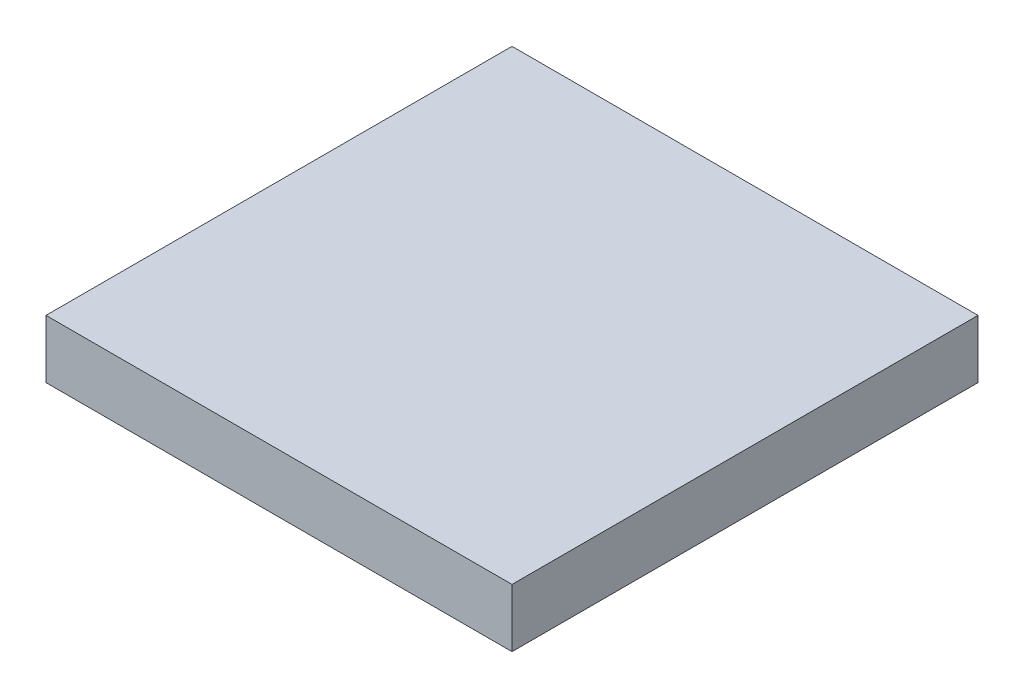
SolidWorks part; units mm, degrees
ref_plane "Front Plane" through (0, 0, 0) normal (0, 0, 1) x (1, 0, 0)
ref_plane "Top Plane" through (0, 0, 0) normal (0, 1, 0) x (1, 0, 0)
ref_plane "Right Plane" through (0, 0, 0) normal (1, 0, 0) x (0, 0, -1)
sketch "Sketch1" plane through (0, 0, 0) normal (0, 1, 0) x (1, 0, 0)
  line L0 (0, 0) -> (20, 0)
  line L1 (20, 0) -> (20, 20)
  line L2 (20, 20) -> (0, 20)
  line L3 (0, 20) -> (0, 0)
  dimension "D1" = 20
  dimension "D2" = 20
extrude "Boss-Extrude1" add sketch "Sketch1" along normal blind 2.5
